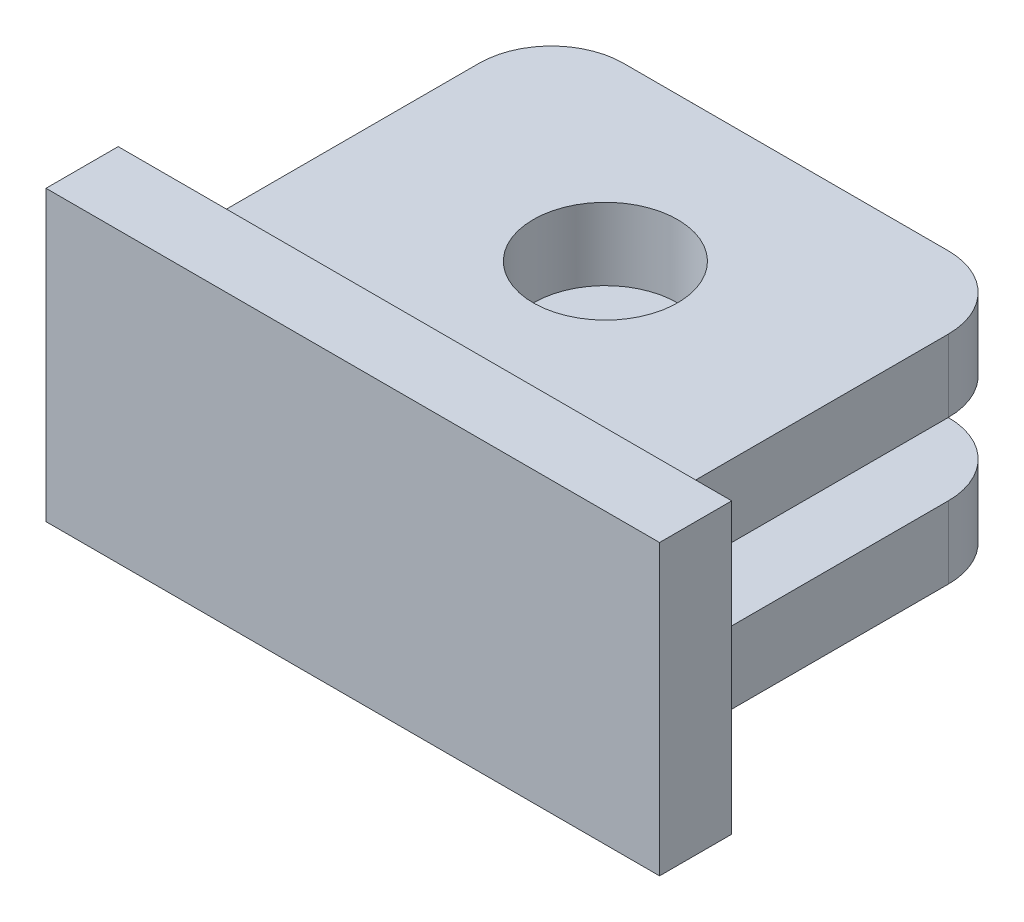
SolidWorks part; units mm, degrees
material "AISI 1020"
ref_plane "Ön Düzlem" through (0, 0, 0) normal (0, 0, 1) x (1, 0, 0)
ref_plane "Üst Düzlem" through (0, 0, 0) normal (0, 1, 0) x (1, 0, 0)
ref_plane "Sağ Düzlem" through (0, 0, 0) normal (1, 0, 0) x (0, 0, -1)
sketch "Çizim1" plane through (0, 0, 0) normal (0, 0, 1) x (1, 0, 0)
  line L1 (0, 0) -> (170, 0)
  line L2 (0, 0) -> (0, 200)
  line L3 (0, 200) -> (170, 200)
  line L4 (170, 0) -> (170, 200)
  dimension "D1" = 170
  dimension "D2" = 200
extrude "Yükseklik-Ekstrüzyon1" add sketch "Çizim1" along normal blind 20
sketch "Çizim2" plane through (0, 0, 0) normal (0, 0, -1) x (-1, 0, 0)
  line L0 (-150, 150) -> (-150, 130)
  line L1 (-150, 130) -> (-20, 130)
  line L2 (-20, 130) -> (-20, 150)
  line L3 (-20, 150) -> (-150, 150)
  line L4 (-170, 200) -> (0, 200) construction
  line L6 (-170, 0) -> (-170, 200) construction
  dimension "D1" = 20
  dimension "D2" = 50
  dimension "D3" = 130
  dimension "D4" = 20
extrude "Yükseklik-Ekstrüzyon2" add sketch "Çizim2" along normal blind 100
fillet "Radyus1" radius 20 2 edges at (20, 140, -100) (150, 140, -100)
sketch "Çizim3" plane through (0, 150, 0) normal (0, 1, 0) x (1, 0, 0)
  line L0 (85, 100) -> (85, 0) construction
  line L1 (40, 100) -> (130, 100) construction
  line L2 (20, 0) -> (150, 0) construction
  line L3 (20, 40) -> (150, 40) construction
  line L4 (20, 80) -> (20, 0) construction
  line L5 (150, 80) -> (150, 0) construction
  circle A0 centre (85, 50) radius 20
  dimension "D1" = 40
extrude "Kes-Ekstrüzyon1" cut sketch "Çizim3" against normal blind 100
ref_plane "Düzlem1" through (0, 110, 0) normal (0, -1, 0) x (-1, 0, 0)
sketch "Çizim4" plane through (0, 110, 0) normal (0, -1, 0) x (-1, 0, 0)
  line L4 (-20, 0) -> (-20, 80)
  line L5 (-40, 100) -> (-130, 100)
  line L6 (-150, 80) -> (-150, 0)
  line L7 (-150, 0) -> (-20, 0)
  line L8 (-20, 0) -> (-20, 80)
  line L9 (-40, 100) -> (-130, 100)
  line L10 (-150, 80) -> (-150, 0)
  line L11 (-150, 0) -> (-20, 0)
  circle A0 centre (-85, 50) radius 20 construction
  circle A1 centre (-85, 50) radius 20
  arc A2 (-20, 80) -> (-40, 100) centre (-40, 80) ccw
  arc A3 (-130, 100) -> (-150, 80) centre (-130, 80) ccw
  arc A4 (-20, 80) -> (-40, 100) centre (-40, 80) ccw
  arc A5 (-130, 100) -> (-150, 80) centre (-130, 80) ccw
  dimension "D1" = 0
extrude "Yükseklik-Ekstrüzyon3" add sketch "Çizim4" along normal blind 20
sketch "Çizim5" plane through (0, 0, 0) normal (0, 0, -1) x (-1, 0, 0)
  line L0 (-170, 160) -> (0, 160)
  line L1 (-170, 0) -> (-170, 200) construction
  line L2 (0, 200) -> (0, 0) construction
  line L3 (-170, 80) -> (0, 80)
  line L5 (-170, 200) -> (0, 200) construction
  line L6 (0, 0) -> (-170, 0) construction
  line L7 (-170, 80) -> (-170, 0)
  line L8 (0, 80) -> (0, 0)
  line L9 (0, 200) -> (0, 160)
  line L10 (-170, 200) -> (0, 200)
  line L11 (-170, 200) -> (-170, 160)
  line L12 (0, 0) -> (-170, 0)
  dimension "D1" = 40
  dimension "D2" = 80
extrude "Kes-Ekstrüzyon2" cut sketch "Çizim5" against normal blind 79
